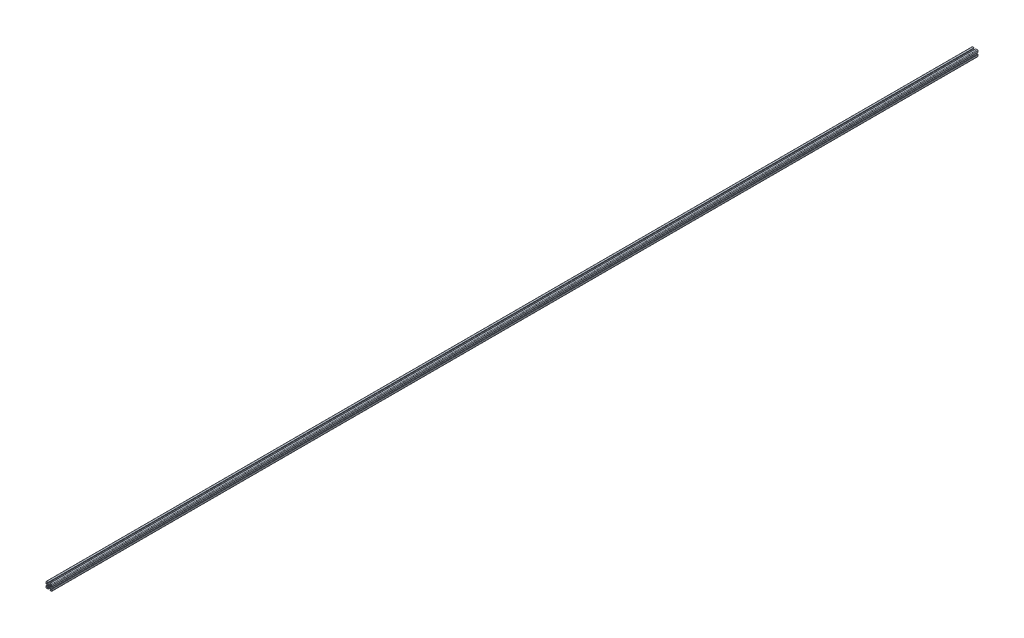
SolidWorks part; units mm, degrees
ref_plane "Front Plane" through (0, 0, 0) normal (0, 0, 1) x (1, 0, 0)
ref_plane "Top Plane" through (0, 0, 0) normal (0, 1, 0) x (1, 0, 0)
ref_plane "Right Plane" through (0, 0, 0) normal (1, 0, 0) x (0, 0, -1)
sketch "Sketch1" plane through (0, 0, 0) normal (0, 0, 1) x (1, 0, 0)
  line L0 (0, 0) -> (0, 10) construction
  line L1 (0, 0) -> (10, 0) construction
  line L2 (0, 0) -> (-10, 10) construction
  line L3 (-7.9302, 9.9988) -> (-3.2721, 9.8361)
  line L4 (-10, 10) -> (0, 10) construction
  line L6 (-2.8352, 8.0198) -> (-4.953, 8.0937)
  line L10 (0, 3.6) -> (-1.1022, 3.6)
  line L11 (-3.2236, 4.4787) -> (-5.5244, 6.7796)
  line L24 (0, 0) -> (-10, 0) construction
  line L25 (-10, 0) -> (0, 0) construction
  line L26 (0, 0) -> (0, -10) construction
  line L27 (-10, -10) -> (-10, 10) construction
  line L28 (0, 10) -> (10, 10) construction
  line L29 (-2.5249, 8.3091) -> (-2.5005, 9.0087)
  line L30 (-10, -10) -> (10, -10) construction
  arc A0 (-9.4142, 9.4142) -> (-7.9302, 9.9988) centre (-8, 8) cw
  arc A5 (-3.2721, 9.8361) -> (-2.5005, 9.0087) centre (-3.3, 9.0366) cw
  arc A6 (-1.1022, 3.6) -> (-3.2236, 4.4787) centre (-1.1022, 6.6) cw
  circle A16 centre (0, 0) radius 2.15
  arc A18 (-5.5244, 6.7796) -> (-4.953, 8.0937) centre (-4.9799, 7.3241) cw
  arc A20 (-2.8352, 8.0198) -> (-2.5249, 8.3091) centre (-2.8247, 8.3196) ccw
  point P15 (0, 0)
  point P42 (-2.3449, 3.6)
  point P80 (-10, 0)
  point P85 (0, -10)
  point P88 (0, -10)
  dimension "D11" = 2
  dimension "D15" = 3
  dimension "Center Hole Diameter" = 4.3
  dimension "D7" = 0.8
  dimension "D8" = 0.3
  dimension "D4" = 0.7701
  dimension "D1" = 45
  dimension "D2" = 2
  dimension "Rail Width" = 20
  dimension "T-Slot Depth" = 6.4
  dimension "D9" = 1.8
  dimension "Rail Height" = 20
  dimension "D23" = 7.2
  dimension "D5" = 11.5
  dimension "T-Slot Width" = 5
  dimension "D3" = 1.775
  dimension "D6" = 9.9598
sketch "Sketch2" plane through (0, 0, 0) normal (1, 0, 0) x (0, 0, -1)
  line L0 (-1524, 0) -> (1524, 0)
  line L1 (-1524, -10) -> (-1524, 10)
  line L2 (0, 0) -> (0, 10) construction
  line L3 (0, 0) -> (0, 10) construction
  line L4 (1524, -10) -> (1524, 10)
  point P0 (-1494, 0)
  point P3 (0, 0)
  point P7 (1494, 0)
  point P11 (-1524, 0)
  point P14 (1524, 0)
  dimension "D1" = 30
  dimension "Length" = 3048
sketch "Sketch3" plane through (0, 0, 0) normal (0, 0, 1) x (1, 0, 0)
  line L0 (-2.5249, 8.3091) -> (-2.5005, 9.0087) construction
  line L1 (0, 0) -> (-10, 10) construction
  line L2 (0, 0) -> (-10, 10) construction
  line L5 (-7.9302, 9.9988) -> (-3.2721, 9.8361) construction
  line L6 (-2.8352, 8.0198) -> (-4.953, 8.0937) construction
  line L17 (-2.5249, 8.3091) -> (-2.5005, 9.0087)
  line L19 (-2.8352, 8.0198) -> (-4.953, 8.0937)
  line L20 (0, 0) -> (0, 10) construction
  line L21 (-3.6, 0) -> (-2.15, 0)
  line L22 (-3.6, 0) -> (-3.6, 1.1022)
  line L23 (-4.4787, 3.2236) -> (-6.7796, 5.5244)
  line L42 (-3.2236, 4.4787) -> (-5.5244, 6.7796) construction
  line L43 (0, 3.6) -> (-1.1022, 3.6) construction
  line L44 (-7.9302, 9.9988) -> (-3.2721, 9.8361)
  line L47 (-3.2236, 4.4787) -> (-5.5244, 6.7796)
  line L48 (0, 3.6) -> (-1.1022, 3.6)
  line L59 (0, 3.6) -> (0, 2.15)
  line L60 (-9.9988, 7.9302) -> (-9.8361, 3.2721)
  line L61 (-8.0198, 2.8352) -> (-8.0937, 4.953)
  line L62 (-8.3091, 2.5249) -> (-9.0087, 2.5005)
  arc A0 (-7.9302, 9.9988) -> (-9.4142, 9.4142) centre (-8, 8) ccw construction
  arc A1 (-2.8352, 8.0198) -> (-2.5249, 8.3091) centre (-2.8247, 8.3196) ccw construction
  arc A3 (-2.8352, 8.0198) -> (-2.5249, 8.3091) centre (-2.8247, 8.3196) ccw
  arc A5 (-7.9302, 9.9988) -> (-9.9988, 7.9302) centre (-8, 8) ccw
  circle A13 centre (0, 0) radius 2.15 construction
  arc A14 (0, 2.15) -> (-2.15, 0) centre (0, 0) ccw
  arc A15 (-4.4787, 3.2236) -> (-3.6, 1.1022) centre (-6.6, 1.1022) cw
  arc A16 (-8.0937, 4.953) -> (-6.7796, 5.5244) centre (-7.3241, 4.9799) cw
  arc A17 (-9.0087, 2.5005) -> (-9.8361, 3.2721) centre (-9.0366, 3.3) cw
  arc A18 (-8.0198, 2.8352) -> (-8.3091, 2.5249) centre (-8.3196, 2.8247) cw
  arc A36 (-2.5005, 9.0087) -> (-3.2721, 9.8361) centre (-3.3, 9.0366) ccw construction
  arc A38 (-4.953, 8.0937) -> (-5.5244, 6.7796) centre (-4.9799, 7.3241) ccw construction
  arc A39 (-3.2236, 4.4787) -> (-1.1022, 3.6) centre (-1.1022, 6.6) ccw construction
  arc A41 (-2.5005, 9.0087) -> (-3.2721, 9.8361) centre (-3.3, 9.0366) ccw
  arc A43 (-4.953, 8.0937) -> (-5.5244, 6.7796) centre (-4.9799, 7.3241) ccw
  arc A44 (-3.2236, 4.4787) -> (-1.1022, 3.6) centre (-1.1022, 6.6) ccw
extrude "Boss-Extrude1" add sketch "Sketch3" along normal mid plane 3048
pattern_circular "CirPattern1" count 4 over 360 about axis through (0, 0, 0) along (0, 0, 1) of "Boss-Extrude1"
ref_plane "Contact Plane 1" through (0, 10, 0) normal (0, 1, 0) x (1, 0, 0)
ref_plane "Contact Plane 2" through (10, 0, 0) normal (1, 0, 0) x (0, 0, -1)
ref_plane "Contact Plane 3" through (0, -10, 0) normal (0, -1, 0) x (-1, 0, 0)
ref_plane "Contact Plane 4" through (-10, 0, 0) normal (-1, 0, 0) x (0, 0, 1)
equation "\"D1@Sketch2\"=\"Rail Width@Sketch1\"*1.5"
equation "\"D1@Boss-Extrude1\" = \"Length@Sketch2\""
